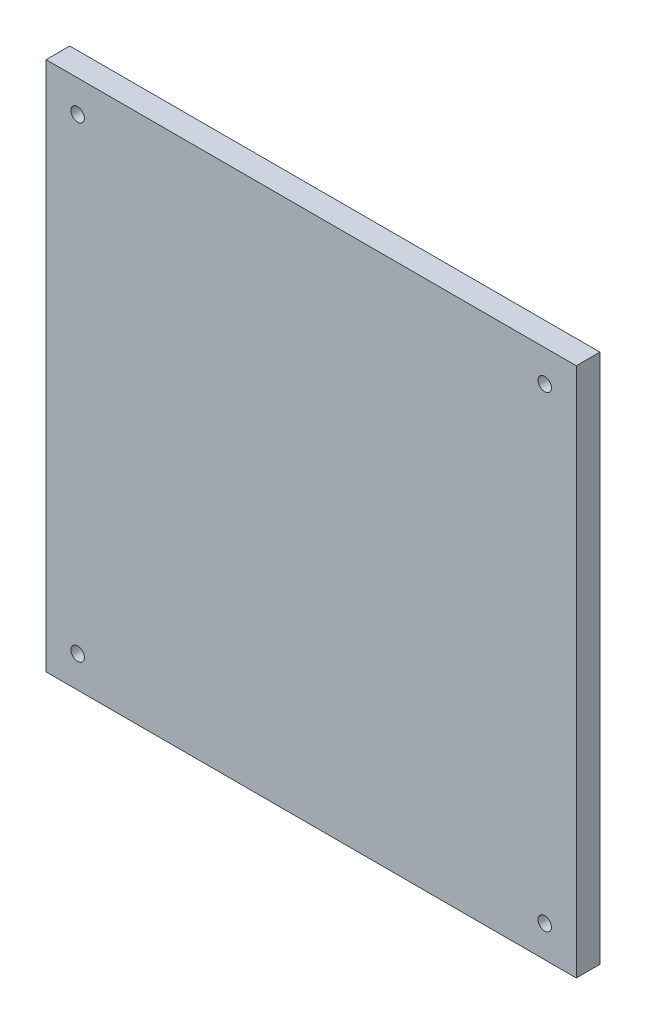
SolidWorks part; units mm, degrees
material "Pine"
ref_plane "Front Plane" through (0, 0, 0) normal (0, 0, 1) x (1, 0, 0)
ref_plane "Top Plane" through (0, 0, 0) normal (0, 1, 0) x (1, 0, 0)
ref_plane "Right Plane" through (0, 0, 0) normal (1, 0, 0) x (0, 0, -1)
sketch "Sketch1" plane through (0, 0, 0) normal (0, 0, 1) x (1, 0, 0)
  line L1 (-133.35, -133.35) -> (133.35, -133.35)
  line L2 (-133.35, -133.35) -> (-133.35, 133.35)
  line L3 (-133.35, 133.35) -> (133.35, 133.35)
  line L4 (133.35, -133.35) -> (133.35, 133.35)
  line L5 (-133.35, -133.35) -> (133.35, 133.35) construction
  line L6 (-133.35, 133.35) -> (133.35, -133.35) construction
  point P0 (0, 0)
  dimension "D1" = 266.7
extrude "Boss-Extrude1" add sketch "Sketch1" along normal blind 11.9062
hole_wizard "1/4 Clearance Hole1" positions "Sketch2" profile "Sketch3" hole size "1/4" standard "ANSI Inch" end condition through all
sketch "Sketch2" plane through (0, 0, 11.9062) normal (0, 0, 1) x (1, 0, 0)
  point P0 (-117.475, 117.475)
  point P2 (117.475, 117.475)
  point P4 (117.475, -117.475)
  point P6 (-117.475, -117.475)
  dimension "D1" = 234.95
  dimension "D2" = 117.475
  dimension "D3" = 234.95
  dimension "D4" = 117.475
sketch "Sketch3" plane through (-117.475, 117.475, 11.9062) normal (1, 0, 0) x (0, -1, 0)
  line L0 (0, 0) -> (0, 11.9062)
  line L1 (0, 11.9062) -> (3.3782, 11.9062)
  line L2 (3.3782, 11.9062) -> (3.3782, 0)
  line L5 (3.3782, 0) -> (0, 0)
  line L11 (0, -6.35) -> (0, 107.95) construction
  dimension "Thru Hole Dia." = 6.7564
  dimension "Thru Hole Depth" = 11.9062
